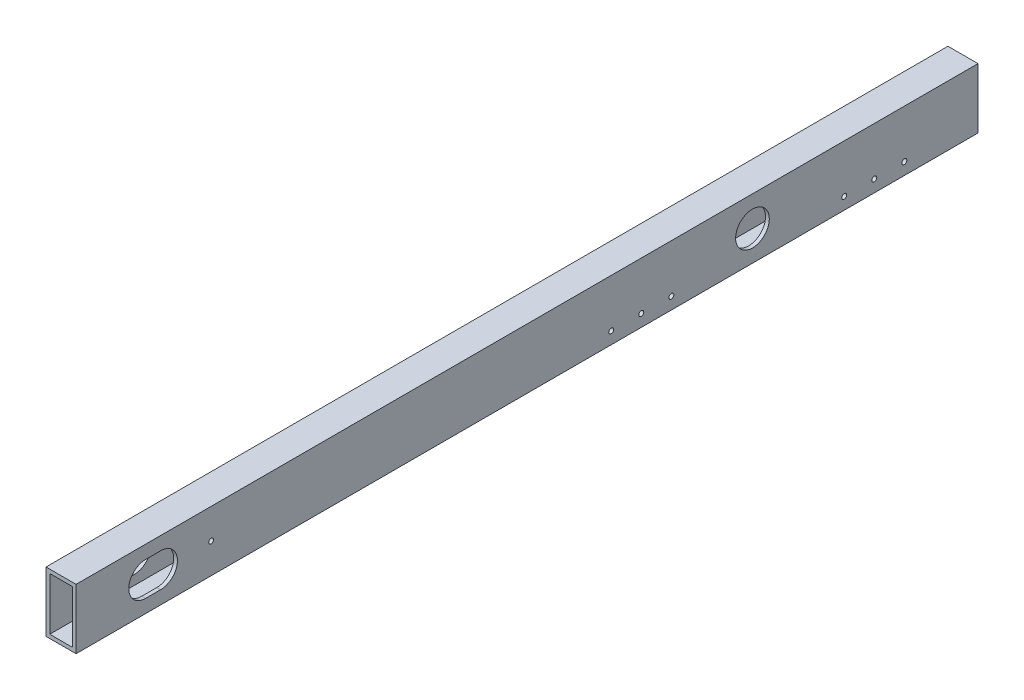
SolidWorks part; units mm, degrees
material "6061 Alloy"
ref_plane "Front Plane" through (0, 0, 0) normal (0, 0, 1) x (1, 0, 0)
ref_plane "Top Plane" through (0, 0, 0) normal (0, 1, 0) x (1, 0, 0)
ref_plane "Right Plane" through (0, 0, 0) normal (1, 0, 0) x (0, 0, -1)
sketch "Sketch1" plane through (0, 0, 0) normal (0, 0, 1) x (1, 0, 0)
  line L0 (0, 25.4) -> (0, 22.225) construction
  line L1 (-12.7, 25.4) -> (12.7, 25.4)
  line L2 (-12.7, 25.4) -> (-12.7, -25.4)
  line L3 (-12.7, -25.4) -> (12.7, -25.4)
  line L4 (12.7, 25.4) -> (12.7, -25.4)
  line L5 (-12.7, 25.4) -> (12.7, -25.4) construction
  line L6 (-12.7, -25.4) -> (12.7, 25.4) construction
  line L7 (-9.525, 22.225) -> (9.525, 22.225)
  line L8 (-9.525, 22.225) -> (-9.525, -22.225)
  line L9 (-9.525, -22.225) -> (9.525, -22.225)
  line L10 (9.525, 22.225) -> (9.525, -22.225)
  line L11 (9.525, 0) -> (12.7, 0) construction
  line L12 (-9.525, 0) -> (-12.7, 0) construction
  line L13 (0, -22.225) -> (0, -25.4) construction
  point P0 (0, 0)
  dimension "D1" = 50.8
  dimension "D2" = 25.4
  dimension "D3" = 3.175
extrude "Boss-Extrude1" add sketch "Sketch1" along normal blind 762
sketch "Sketch2" plane through (0, 25.4, 0) normal (0, 1, 0) x (1, 0, 0)
  line L0 (-26.9875, -190.549) -> (26.9875, -190.549) construction
  line L1 (-12.7, 0) -> (12.7, 0)
  line L2 (-12.7, 0) -> (-12.7, -762)
  line L3 (-12.7, -762) -> (12.7, -762)
  line L4 (12.7, 0) -> (12.7, -762)
  line L5 (-26.4963, -703.2466) -> (26.4963, -703.2466) construction
  line L6 (0, -703.2466) -> (0, -190.549) construction
  line L7 (0, 0) -> (0, -190.549) construction
  line L8 (-74.6125, -402.6047) -> (-73.6301, -528.6965) construction
  line L9 (-74.1213, -465.6506) -> (-23.8125, -465.6506) construction
  line L10 (-23.8125, -465.6506) -> (26.9875, -465.6506) construction
  dimension "D1" = 190.549
  dimension "D2" = 512.6976
  dimension "D3" = 126.0917
  dimension "D4" = 50.3088
  dimension "D5" = 50.8
  dimension "D6" = 53.975
  dimension "D7" = 52.9926
  dimension "D8" = 275.1016
ref_plane "Plane1" through (12.7, 0, 0) normal (1, 0, 0) x (0, 0, -1)
sketch "Sketch4" plane through (12.7, 0, 0) normal (1, 0, 0) x (0, 0, -1)
  line L0 (-690.548, 25.4) -> (-690.548, 0) construction
  line L1 (-703.2466, 25.4) -> (-190.549, 25.4) construction
  line L2 (-190.549, 25.4) -> (-190.549, 0) construction
  line L3 (0, 25.4) -> (-190.549, 25.4) construction
  line L4 (-190.549, 0) -> (0, 0) construction
  line L5 (0, -25.4) -> (0, 25.4) construction
  line L6 (-190.549, 0) -> (-690.548, 0) construction
  line L7 (-690.548, 0) -> (-703.248, 0) construction
  line L8 (-703.248, 0) -> (-703.248, 14.224) construction
  line L9 (-703.248, 14.224) -> (-690.548, 14.224)
  line L10 (-703.248, 0) -> (-703.248, -14.224) construction
  line L11 (-703.248, -14.224) -> (-690.548, -14.224)
  line L12 (-676.324, 0) -> (-647.876, 0) construction
  circle A1 centre (-190.549, 0) radius 14.224
  arc A2 (-703.248, 14.224) -> (-703.248, -14.224) centre (-703.248, 0) ccw
  arc A3 (-690.548, -14.224) -> (-690.548, 14.224) centre (-690.548, 0) ccw
  circle A4 centre (-647.876, 0) radius 2.032
  dimension "D1" = 14.224
  dimension "D5" = 28.448
  dimension "D6" = 28.448
  dimension "D7" = 4.064
  dimension "D2" = 499.999
  dimension "D3" = 190.549
  dimension "D4" = 12.7
extrude "Cut-Extrude1" cut sketch "Sketch4" against normal up to surface (25.4 mm away) up to face at (-12.7, 0, 381)
sketch "Sketch5" plane through (0, -25.4, 0) normal (0, -1, 0) x (1, 0, 0)
  line L0 (-12.7, 0) -> (-12.7, 762) construction
  line L2 (0, 264.16) -> (0, 328.0394) construction
  line L4 (-12.7, 264.16) -> (12.7, 264.16) construction
  line L5 (12.7, 0) -> (12.7, 762) construction
  line L6 (2.54, 264.16) -> (2.54, 340.36) construction
  line L7 (0, 703.2466) -> (0, 190.549) construction
  circle A0 centre (2.54, 264.16) radius 2.0955
  circle A1 centre (2.54, 289.56) radius 2.0955
  circle A2 centre (2.54, 314.96) radius 2.0955
  circle A3 centre (-2.54, 264.16) radius 2.0955
  circle A4 centre (-2.54, 289.56) radius 2.0955
  circle A5 centre (-2.54, 314.96) radius 2.0955
  dimension "D4" = 4.191
  dimension "D1" = 264.16
  dimension "D3" = 76.2
  dimension "D6" = 10.16
  dimension "D5" = 3
extrude "Cut-Extrude2" cut sketch "Sketch5" against normal up to surface (3.175 mm away) up to face at (0, -22.225, 381)
sketch "Sketch7" plane through (12.7, 0, 0) normal (1, 0, 0) x (0, 0, -1)
  line L0 (0, -15.24) -> (-25.4, -15.24) construction
  line L1 (0, -25.4) -> (0, 25.4) construction
  line L2 (-259.08, -15.24) -> (-297.18, -15.24) construction
  line L3 (-762, -25.4) -> (0, -25.4) construction
  line L4 (-149.86, -15.24) -> (-25.4, -15.24) construction
  line L5 (-149.86, -15.24) -> (-259.08, -15.24) construction
  circle A0 centre (-259.08, -15.24) radius 2.0955
  circle A1 centre (-284.48, -15.24) radius 2.0955
  circle A2 centre (-309.88, -15.24) radius 2.0955
  circle A3 centre (-87.63, -15.24) radius 2.0955
  circle A4 centre (-62.23, -15.24) radius 2.0955
  circle A5 centre (-113.03, -15.24) radius 2.0955
  dimension "D3" = 4.191
  dimension "D1" = 259.08
  dimension "D2" = 38.1
  dimension "D5" = 10.16
  dimension "D6" = 124.46
  dimension "D7" = 25.4
  dimension "D4" = 3
  dimension "D8" = 2
  dimension "D9" = 2
extrude "Cut-Extrude3" cut sketch "Sketch7" against normal up to surface (25.4 mm away) up to face at (-12.7, 0, 176.325)
